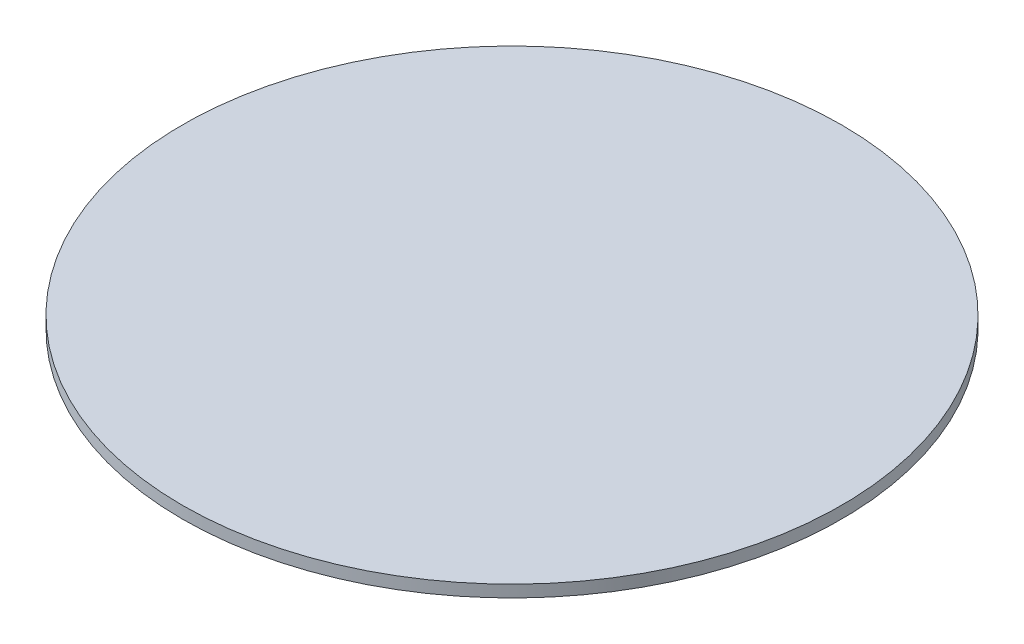
SolidWorks part; units mm, degrees
ref_plane "Front Plane" through (0, 0, 0) normal (0, 0, 1) x (1, 0, 0)
ref_plane "Top Plane" through (0, 0, 0) normal (0, 1, 0) x (1, 0, 0)
ref_plane "Right Plane" through (0, 0, 0) normal (1, 0, 0) x (0, 0, -1)
other "Configuration Table"
sketch "Sketch1" plane through (0, 0, 0) normal (0, 1, 0) x (1, 0, 0)
  circle A0 centre (350, 300) radius 165
extrude "OVEN_kesme_tepsi_halkasi_D330" add sketch "Sketch1" along normal blind 6 from offset 340 separate body
